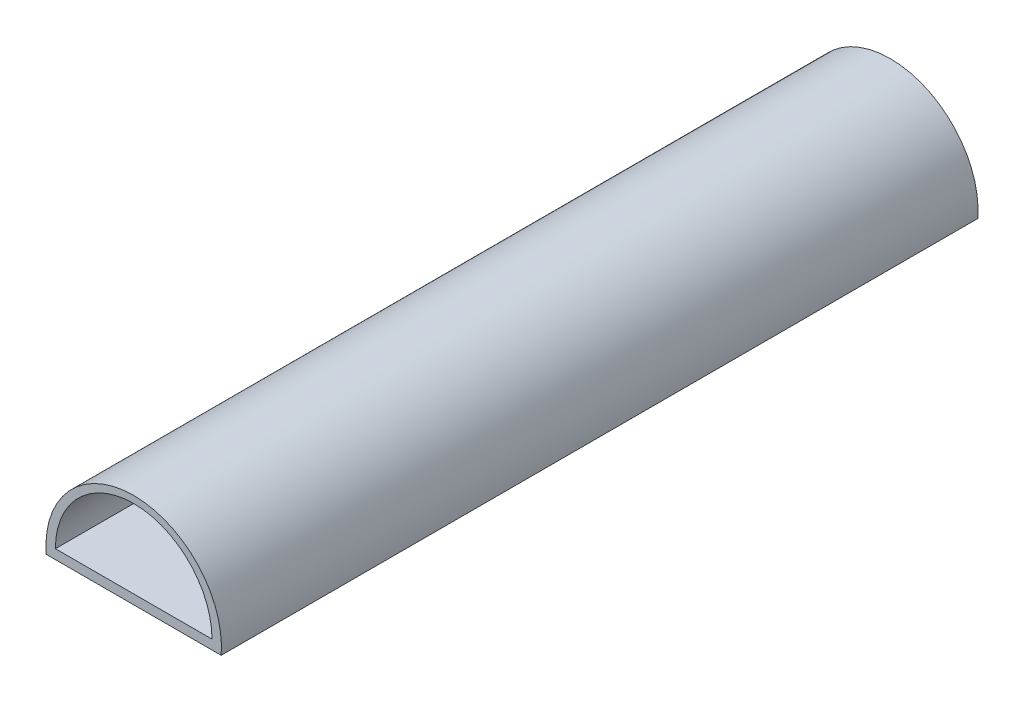
SolidWorks part; units mm, degrees
material "PVC 0.007 Plasticized"
ref_plane "Front Plane" through (0, 0, 0) normal (0, 0, 1) x (1, 0, 0)
ref_plane "Top Plane" through (0, 0, 0) normal (0, 1, 0) x (1, 0, 0)
ref_plane "Right Plane" through (0, 0, 0) normal (1, 0, 0) x (0, 0, -1)
sketch "Sketch1" plane through (0, 0, 0) normal (0, 0, 1) x (1, 0, 0)
  line L0 (-23.1114, -10.0484) -> (6.2574, -10.0484)
  line L2 (-8.427, -8.4609) -> (-21.5715, -8.4609)
  line L3 (-8.427, -8.4609) -> (4.7175, -8.4609)
  arc A0 (-23.1114, -10.0484) -> (6.2574, -10.0484) centre (-8.427, -8.8769) cw
  arc A1 (-21.5715, -8.4609) -> (4.7175, -8.4609) centre (-8.427, -8.4609) cw
extrude "Boss-Extrude2" add sketch "Sketch1" along normal blind 127
